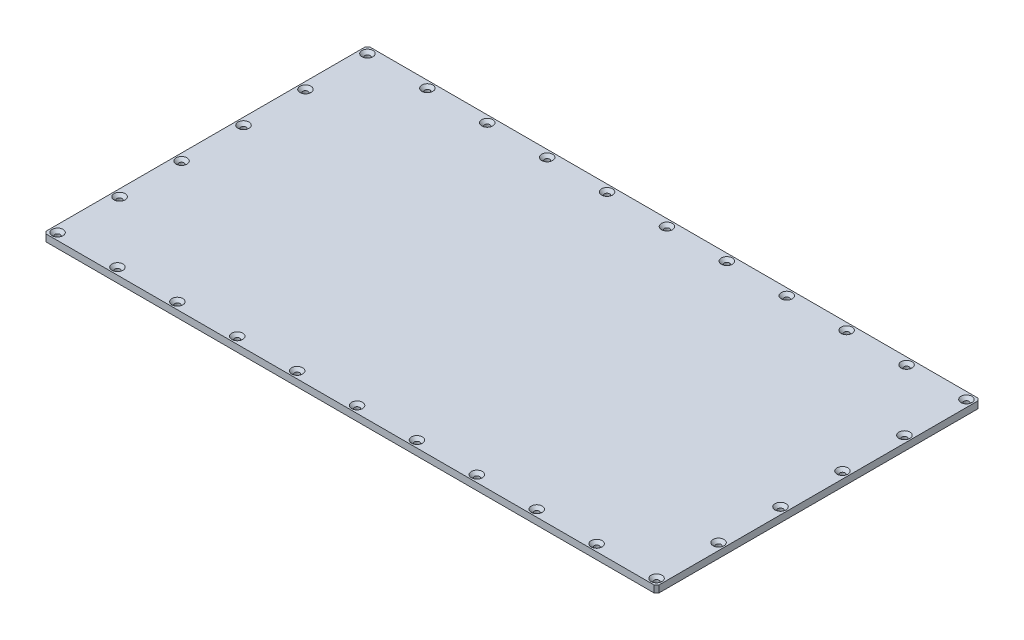
SolidWorks part; units mm, degrees
ref_plane "Front Plane" through (0, 0, 0) normal (0, 0, 1) x (1, 0, 0)
ref_plane "Top Plane" through (0, 0, 0) normal (0, 1, 0) x (1, 0, 0)
ref_plane "Right Plane" through (0, 0, 0) normal (1, 0, 0) x (0, 0, -1)
sketch "Sketch1" plane through (0, 0, 0) normal (0, 1, 0) x (1, 0, 0)
  line L0 (265, -131.75) -> (265, 0)
  line L1 (0, -140) -> (265, -140)
  line L2 (0, -140) -> (0, 0)
  line L3 (0, 0) -> (265, 0)
  line L4 (265, -140) -> (265, -136.25)
  circle A0 centre (6, -26.8) radius 2.25
  circle A1 centre (6, -80.4) radius 2.25
  circle A2 centre (6, -134) radius 2.25
  circle A3 centre (57.8, -134) radius 2.25
  circle A4 centre (109.6, -134) radius 2.25
  circle A5 centre (161.4, -134) radius 2.25
  circle A6 centre (213.2, -134) radius 2.25
  arc A7 (265, -131.75) -> (265, -136.25) centre (265, -134) ccw
  dimension "D3" = 4.5
  dimension "D4" = 4.5
  dimension "D5" = 4.5
  dimension "D6" = 4.5
  dimension "D7" = 4.5
  dimension "D8" = 4.5
  dimension "D9" = 4.5
  dimension "D18" = 4.5
  dimension "D1" = 265
  dimension "D2" = 140
  dimension "D10" = 6
  dimension "D11" = 6
  dimension "D12" = 6
  dimension "D13" = 6
  dimension "D14" = 6
  dimension "D15" = 6
  dimension "D16" = 6
  dimension "D17" = 6
  dimension "D19" = 6
  dimension "D20" = 51.8
  dimension "D21" = 51.8
  dimension "D22" = 51.8
  dimension "D23" = 51.8
  dimension "D24" = 53.6
  dimension "D25" = 53.6
  dimension "D26" = 0
  dimension "D27" = 0
extrude "Boss-Extrude1" add sketch "Sketch1" along normal blind 6 contours L2 L3 L0 A7 L4 L1 | A3 | A4 | A2 | A1 | A0 | A6 | A5
chamfer "Chamfer1" distance 2.5 angle 45 8 edges at (6, 6, 29.05) (6, 6, 82.65) (6, 6, 136.25) (57.8, 6, 136.25) (109.6, 6, 136.25) (161.4, 6, 136.25) (213.2, 6, 136.25) (262.75, 6, 134)
mirror "Mirror3" about plane through (265, 6, 131.75) normal (-1, 0, 0) of bodies 101
mirror "Mirror4" about plane through (0, 6, 0) normal (0, 0, -1) of bodies 104
chamfer "Chamfer2" distance 2 angle 45 4 edges at (0, 3, 140) (530, 3, -140) (0, 3, -140) (530, 3, 140)
equation "\"D4@Sketch1\"=\"D3@Sketch1\""
equation "\"D5@Sketch1\"=\"D3@Sketch1\""
equation "\"D6@Sketch1\"=\"D3@Sketch1\""
equation "\"D7@Sketch1\"=\"D3@Sketch1\""
equation "\"D8@Sketch1\"=\"D3@Sketch1\""
equation "\"D9@Sketch1\"=\"D3@Sketch1\""
equation "\"D18@Sketch1\"=\"D3@Sketch1\""
